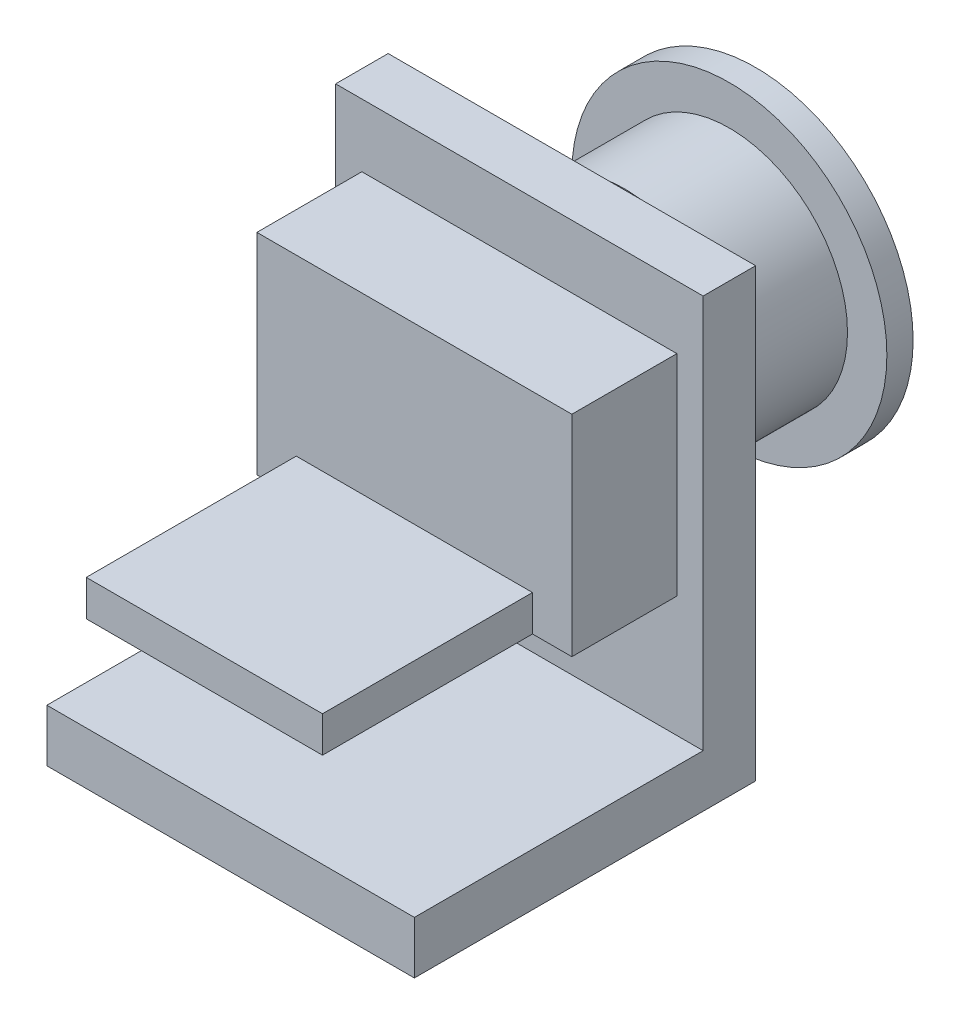
SolidWorks part; units mm, degrees
ref_plane "Front Plane" through (0, 0, 0) normal (0, 0, 1) x (1, 0, 0)
ref_plane "Top Plane" through (0, 0, 0) normal (0, 1, 0) x (1, 0, 0)
ref_plane "Right Plane" through (0, 0, 0) normal (1, 0, 0) x (0, 0, -1)
sketch "Sketch1" plane through (0, 0, 0) normal (0, 0, 1) x (1, 0, 0)
  circle A0 centre (0, 0) radius 19.05
  dimension "D1" = 38.1
extrude "Boss-Extrude2" add sketch "Sketch1" along normal blind 3.175
sketch "Sketch2" plane through (0, 0, 3.175) normal (0, 0, 1) x (1, 0, 0)
  circle A0 centre (0, 0) radius 14.2875
  dimension "D1" = 28.575
extrude "Boss-Extrude3" add sketch "Sketch2" along normal blind 12.7
sketch "Sketch5" plane through (0, 0, 15.875) normal (0, 0, 1) x (1, 0, 0)
  circle A0 centre (0, 0) radius 12.7
  dimension "D1" = 25.4
extrude "Boss-Extrude4" add sketch "Sketch5" along normal blind 6.35
sketch "Sketch6" plane through (0, 0, 22.225) normal (0, 0, 1) x (1, 0, 0)
  line L0 (-22.225, 20.5012) -> (22.225, 20.5012)
  line L1 (22.225, 20.5012) -> (22.225, -33.4738)
  line L2 (22.225, -33.4738) -> (-22.225, -33.4738)
  line L3 (-22.225, -33.4738) -> (-22.225, 20.5012)
  dimension "D1" = 53.975
  dimension "D2" = 44.45
  dimension "D3" = 22.225
extrude "Boss-Extrude5" add sketch "Sketch6" along normal blind 6.35
sketch "Sketch7" plane through (0, 0, 28.575) normal (0, 0, 1) x (1, 0, 0)
  line L0 (-22.225, -27.1238) -> (22.225, -27.1238)
  line L1 (-22.225, 20.5012) -> (-22.225, -33.4738) construction
  line L2 (22.225, -33.4738) -> (22.225, 20.5012) construction
  line L3 (22.225, -27.1238) -> (22.225, -33.4738)
  line L4 (-22.225, -33.4738) -> (22.225, -33.4738) construction
  line L5 (22.225, -33.4738) -> (-22.225, -33.4738)
  line L6 (-22.225, -33.4738) -> (-22.225, -27.1238)
  dimension "D1" = 6.35
extrude "Boss-Extrude6" add sketch "Sketch7" along normal blind 34.925
sketch "Sketch8" plane through (0, 0, 28.575) normal (0, 0, 1) x (1, 0, 0)
  line L0 (-19.05, 12.8812) -> (19.05, 12.8812)
  line L1 (19.05, 12.8812) -> (19.05, -12.5188)
  line L2 (19.05, -12.5188) -> (-19.05, -12.5188)
  line L3 (-19.05, -12.5188) -> (-19.05, 12.8812)
  line L4 (22.225, 20.5012) -> (-22.225, 20.5012) construction
  dimension "D1" = 38.1
  dimension "D2" = 19.05
  dimension "D3" = 25.4
  dimension "D4" = 7.62
extrude "Boss-Extrude7" add sketch "Sketch8" along normal blind 12.7
sketch "Sketch9" plane through (0, 0, 41.275) normal (0, 0, 1) x (1, 0, 0)
  line L0 (-14.2875, -8.1756) -> (14.2875, -8.1756)
  line L1 (14.2875, -8.1756) -> (14.2875, -12.5188)
  line L2 (-19.05, -12.5188) -> (19.05, -12.5188) construction
  line L3 (14.2875, -12.5188) -> (-14.2875, -12.5188)
  line L4 (-14.2875, -12.5188) -> (-14.2875, -8.1756)
  point P2 (0, 0)
  dimension "D1" = 28.575
  dimension "D2" = 14.2875
extrude "Boss-Extrude9" add sketch "Sketch9" along normal blind 25.4
